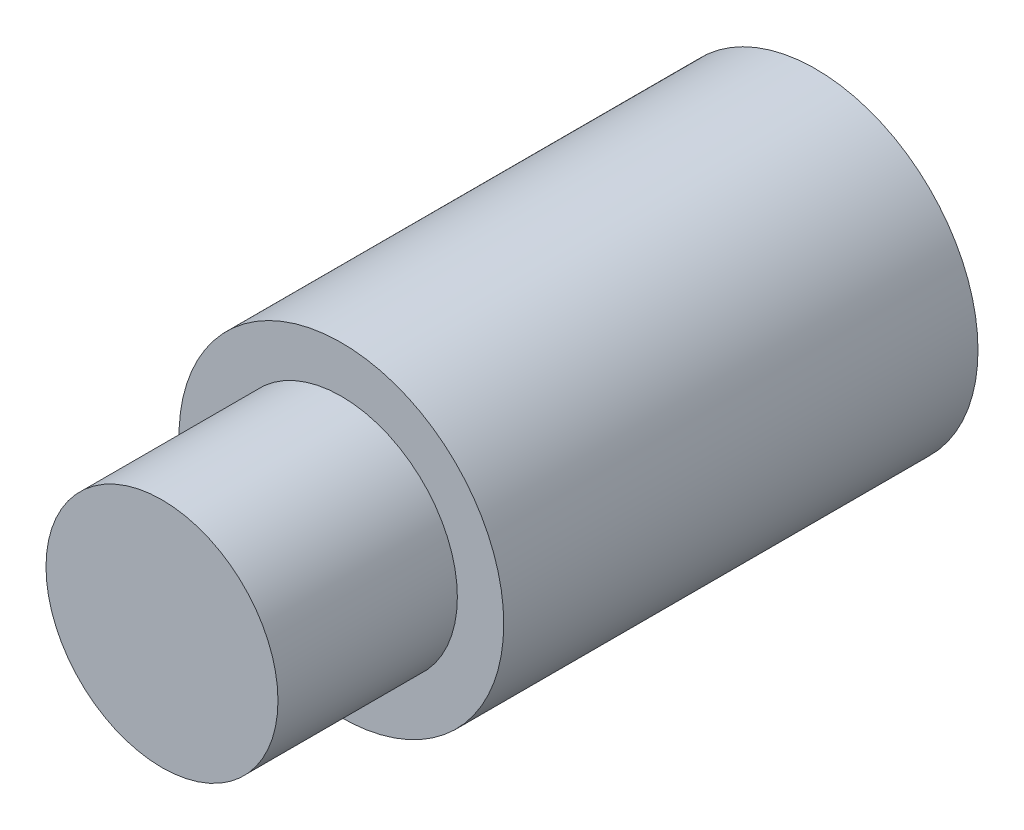
SolidWorks part; units mm, degrees
ref_plane "Front Plane" through (0, 0, 0) normal (0, 0, 1) x (1, 0, 0)
ref_plane "Top Plane" through (0, 0, 0) normal (0, 1, 0) x (1, 0, 0)
ref_plane "Right Plane" through (0, 0, 0) normal (1, 0, 0) x (0, 0, -1)
sketch "Sketch1" plane through (0, 0, 0) normal (0, 0, 1) x (1, 0, 0)
  circle A0 centre (0, 0) radius 4.0005
  dimension "D1" = 8.001
extrude "Boss-Extrude1" add sketch "Sketch1" along normal blind 11.684
sketch "Sketch2" plane through (0, 0, 11.684) normal (0, 0, 1) x (1, 0, 0)
  circle A0 centre (0, 0) radius 2.8575
  dimension "D1" = 5.715
extrude "Boss-Extrude2" add sketch "Sketch2" along normal blind 4.4196
